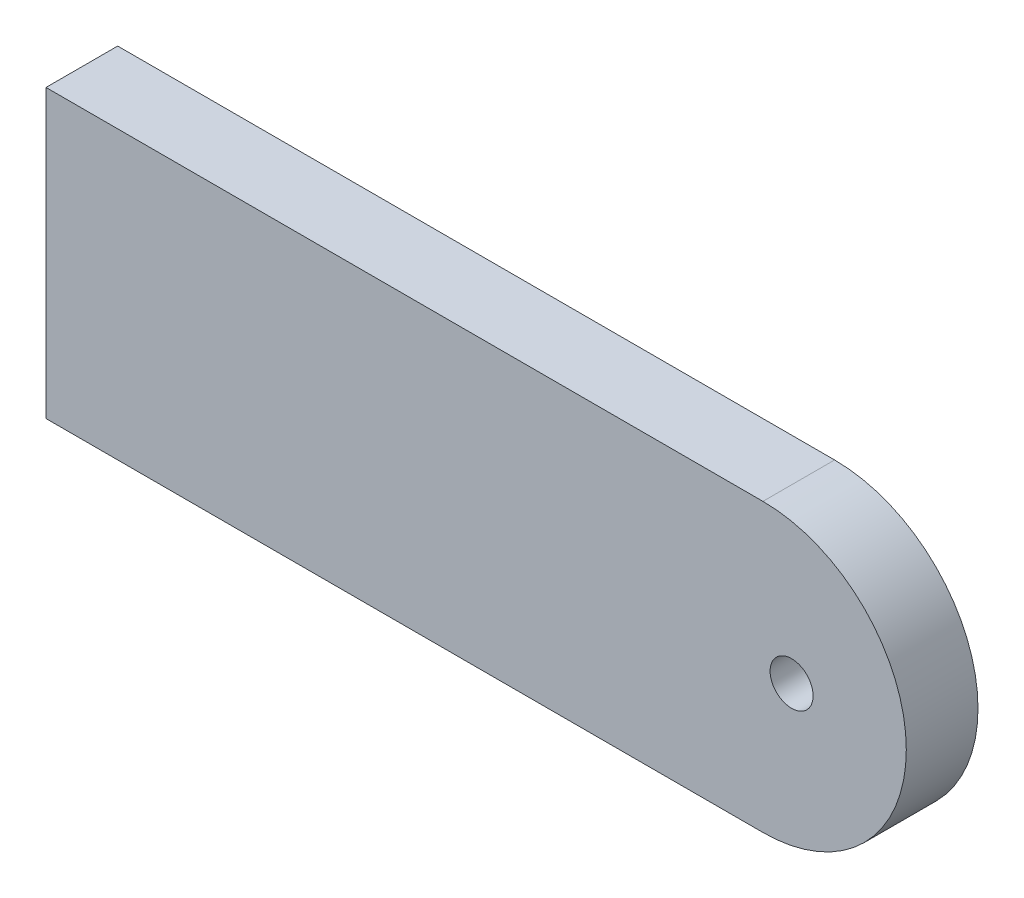
SolidWorks part; units mm, degrees
ref_plane "Front Plane" through (0, 0, 0) normal (0, 0, 1) x (1, 0, 0)
ref_plane "Top Plane" through (0, 0, 0) normal (0, 1, 0) x (1, 0, 0)
ref_plane "Right Plane" through (0, 0, 0) normal (1, 0, 0) x (0, 0, -1)
sketch "Sketch1" plane through (0, 0, 0) normal (0, 0, 1) x (1, 0, 0)
  line L1 (0, 0) -> (50, 0)
  line L2 (0, 0) -> (0, 20)
  line L3 (0, 20) -> (50, 20)
  arc A0 (50, 0) -> (50, 20) centre (50, 10) ccw
  dimension "D1" = 20
  dimension "D2" = 50
extrude "Boss-Extrude1" add sketch "Sketch1" along normal blind 5
sketch "Sketch2" plane through (0, 0, 5) normal (0, 0, 1) x (1, 0, 0)
  line L0 (50, 20) -> (0, 20) construction
  circle A0 centre (52, 10) radius 1.5
  arc A2 (50, 0) -> (50, 20) centre (50, 10) ccw construction
  point P7 (60, 10)
  dimension "D1" = 3
  dimension "D2" = 10
  dimension "D3" = 8
extrude "Cut-Extrude1" cut sketch "Sketch2" against normal blind 5
